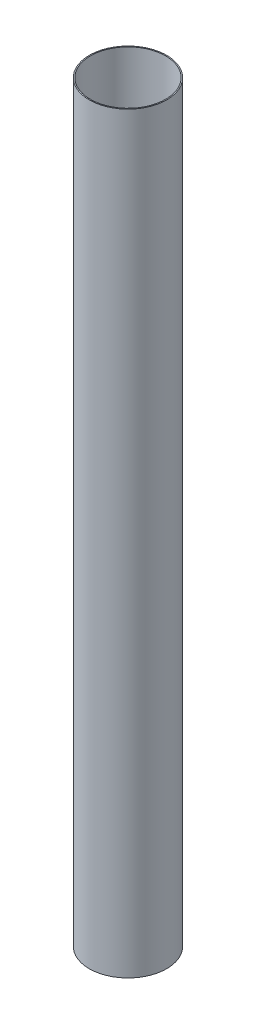
SolidWorks part; units mm, degrees
material "A-Glass Fiber"
ref_plane "Front Plane" through (0, 0, 0) normal (0, 0, 1) x (1, 0, 0)
ref_plane "Top Plane" through (0, 0, 0) normal (0, 1, 0) x (1, 0, 0)
ref_plane "Right Plane" through (0, 0, 0) normal (1, 0, 0) x (0, 0, -1)
sketch "Sketch1" plane through (0, 0, 0) normal (0, 1, 0) x (1, 0, 0)
  circle A0 centre (0, 0) radius 78.359
  circle A1 centre (0, 0) radius 76.2
  dimension "D1" = 152.4
  dimension "D2" = 156.718
extrude "Boss-Extrude1" add sketch "Sketch1" along normal blind 1524
